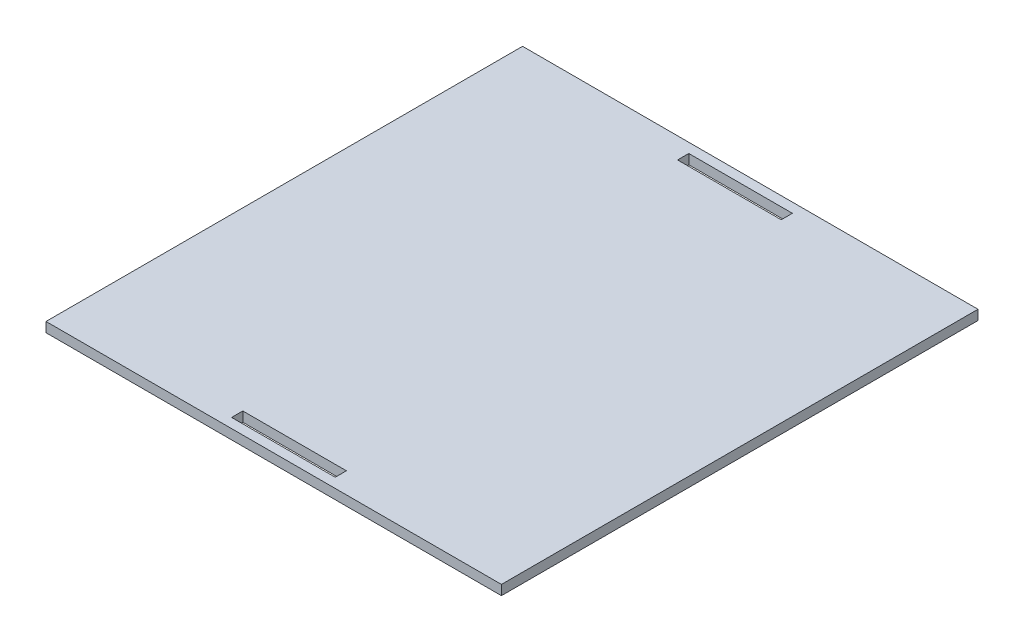
SolidWorks part; units mm, degrees
ref_plane "Front Plane" through (0, 0, 0) normal (0, 0, 1) x (1, 0, 0)
ref_plane "Top Plane" through (0, 0, 0) normal (0, 1, 0) x (1, 0, 0)
ref_plane "Right Plane" through (0, 0, 0) normal (1, 0, 0) x (0, 0, -1)
sketch "Sketch1" plane through (0, 0, 0) normal (0, 1, 0) x (1, 0, 0)
  line L0 (-69.7865, 66.4972) -> (69.7865, 66.4972) construction
  line L1 (69.7865, -73.025) -> (-69.7865, -73.025)
  line L2 (69.7865, -73.025) -> (69.7865, 73.025)
  line L3 (69.7865, 73.025) -> (-69.7865, 73.025)
  line L4 (-69.7865, -73.025) -> (-69.7865, 73.025)
  line L5 (69.7865, -73.025) -> (-69.7865, 73.025) construction
  line L6 (69.7865, 73.025) -> (-69.7865, -73.025) construction
  line L7 (-69.7865, -66.4972) -> (69.7865, -66.4972) construction
  line L8 (-69.7865, 66.4972) -> (-69.7865, -66.4972) construction
  line L9 (69.7865, 66.4972) -> (69.7865, -66.4972) construction
  line L10 (0, 66.6242) -> (0, -66.6242) construction
  line L11 (-15.875, 70.0532) -> (15.875, 70.0532)
  line L12 (-15.875, 70.0532) -> (-15.875, 66.6242)
  line L13 (-15.875, 66.6242) -> (15.875, 66.6242)
  line L14 (15.875, 70.0532) -> (15.875, 66.6242)
  line L15 (-15.875, -66.6242) -> (15.875, -66.6242)
  line L16 (-15.875, -66.6242) -> (-15.875, -70.0532)
  line L17 (-15.875, -70.0532) -> (15.875, -70.0532)
  line L18 (15.875, -66.6242) -> (15.875, -70.0532)
  point P0 (0, 0)
  point P10 (69.7865, 0)
  point P11 (69.7865, 0)
  point P16 (0, 66.6242)
  point P17 (0, 0)
  dimension "D1" = 139.573
  dimension "D2" = 146.05
  dimension "D3" = 132.9944
  dimension "D4" = 3.429
  dimension "D5" = 31.75
  dimension "D6" = 0.254
extrude "Boss-Extrude1" add sketch "Sketch1" along normal blind 2.9972
